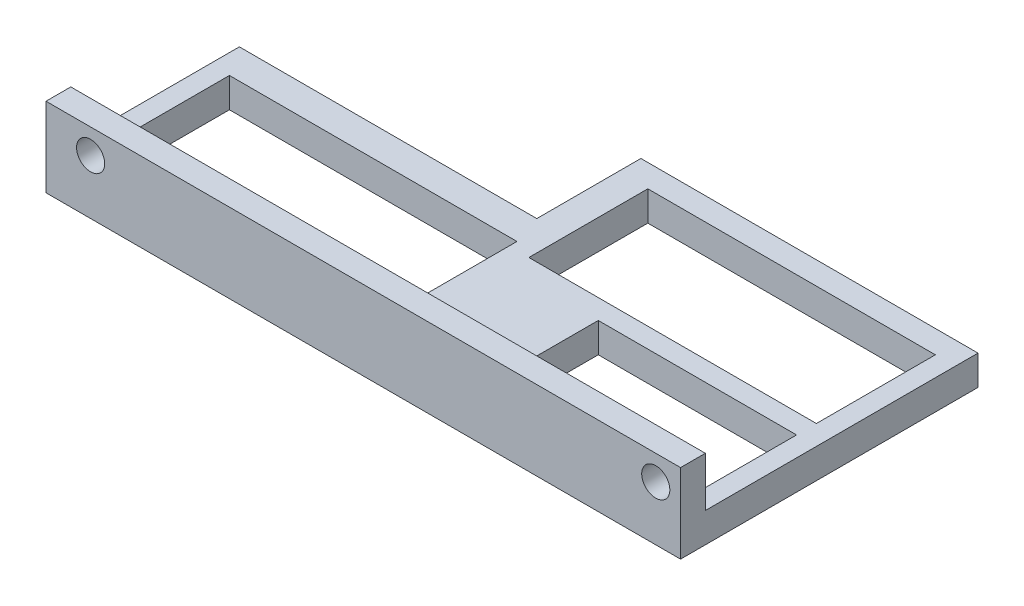
SolidWorks part; units mm, degrees
ref_plane "Front Plane" through (0, 0, 0) normal (0, 0, 1) x (1, 0, 0)
ref_plane "Top Plane" through (0, 0, 0) normal (0, 1, 0) x (1, 0, 0)
ref_plane "Right Plane" through (0, 0, 0) normal (1, 0, 0) x (0, 0, -1)
sketch "Sketch1" plane through (0, 0, 0) normal (0, 1, 0) x (1, 0, 0)
  line L1 (0, 0) -> (64, 0)
  line L2 (0, 0) -> (0, 30)
  line L3 (0, 30) -> (64, 30)
  line L4 (64, 0) -> (64, 30)
  dimension "D1" = 64
  dimension "D2" = 30
extrude "Boss-Extrude1" add sketch "Sketch1" along normal blind 3
sketch "Sketch2" plane through (0, 3, 0) normal (0, 1, 0) x (1, 0, 0)
  line L0 (64, 0) -> (64, 30) construction
  line L1 (2, 16.5) -> (31, 16.5)
  line L2 (2, 16.5) -> (2, 4)
  line L3 (2, 4) -> (31, 4)
  line L5 (33, 27.7) -> (62, 27.7)
  line L7 (33, 15.7) -> (62, 15.7)
  line L8 (62, 27.7) -> (62, 15.7)
  line L9 (42, 13.7) -> (62, 13.7)
  line L10 (42, 13.7) -> (42, 4)
  line L11 (42, 4) -> (62, 4)
  line L12 (62, 13.7) -> (62, 4)
  line L13 (0, 0) -> (64, 0) construction
  line L14 (33, 15.7) -> (33, 27.7)
  line L15 (0, 30) -> (30, 30)
  line L16 (0, 30) -> (0, 19.5)
  line L17 (0, 19.5) -> (30, 19.5)
  line L18 (30, 30) -> (30, 19.5)
  line L19 (31, 4) -> (31, 16.5)
  line L20 (0, 30) -> (0, 0) construction
  dimension "D1" = 9.7
  dimension "D2" = 12
  dimension "D3" = 12.5
  dimension "D4" = 29
  dimension "D5" = 29
  dimension "D6" = 20
  dimension "D7" = 2
  dimension "D9" = 2
  dimension "D10" = 4
  dimension "D11" = 2
  dimension "D12" = 3
  dimension "3" = 3
extrude "Cut-Extrude1" cut sketch "Sketch2" against normal up to next
sketch "Sketch3" plane through (0, 3, 0) normal (0, 1, 0) x (1, 0, 0)
  line L0 (0, 19.5) -> (0, 0) construction
  line L1 (0, 2.5) -> (64, 2.5)
  line L2 (0, 2.5) -> (0, 0)
  line L3 (0, 0) -> (64, 0)
  line L4 (64, 2.5) -> (64, 0)
  line L5 (64, 0) -> (64, 30) construction
  line L6 (0, 0) -> (64, 0) construction
  dimension "D1" = 2.5
extrude "Boss-Extrude3" add sketch "Sketch3" along normal blind 5
sketch "Sketch4" plane through (0, 0, 0) normal (0, 0, 1) x (1, 0, 0)
  line L0 (0, 8) -> (64, 8) construction
  line L2 (0, 8) -> (0, 0) construction
  line L3 (64, 8) -> (64, 0) construction
  circle A0 centre (61.5, 5.5) radius 1.4192
  circle A1 centre (4.5, 5.5) radius 1.4192
  point P4 (0, 0)
  point P7 (0, 0)
  point P9 (0, 3.6956)
  dimension "D1" = 2.5
  dimension "D2" = 4.5
  dimension "D3" = 2.5
extrude "Cut-Extrude2" cut sketch "Sketch4" against normal up to next
